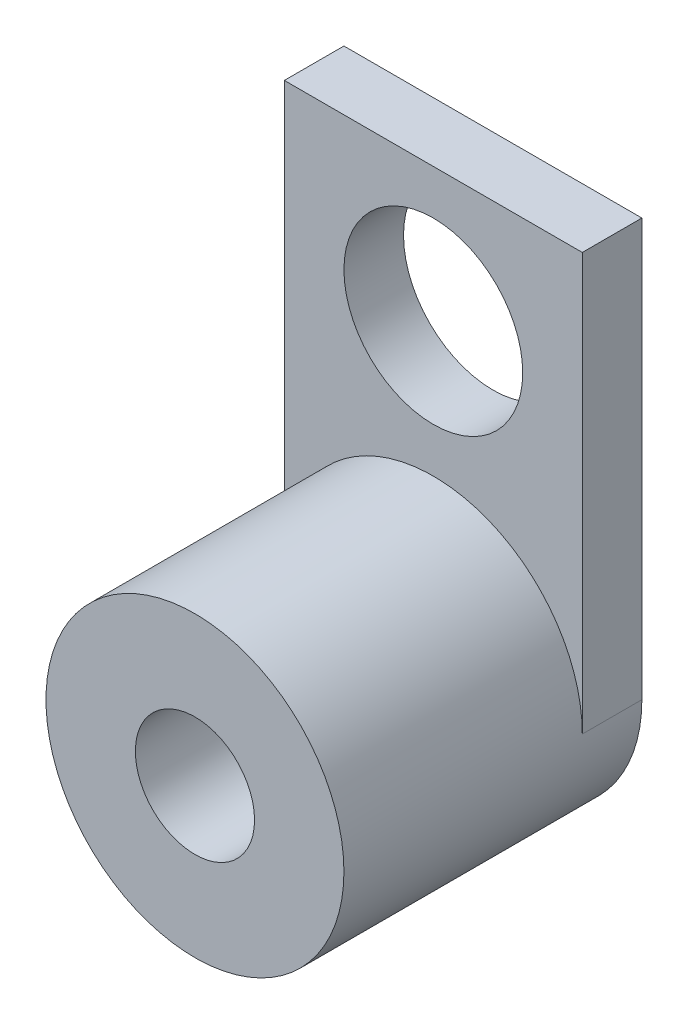
SolidWorks part; units mm, degrees
ref_plane "Front Plane" through (0, 0, 0) normal (1, 0, 0) x (0, 1, 0)
ref_plane "Top Plane" through (0, 0, 0) normal (0, 0, 1) x (0, 1, 0)
ref_plane "Right Plane" through (0, 0, 0) normal (0, 1, 0) x (-1, 0, 0)
sketch "Sketch3" plane through (0, 0, 0) normal (0, 0, 1) x (0, 1, 0)
  circle A0 centre (0, 0) radius 63.5
  circle A1 centre (0, 0) radius 25.4
  dimension "D1" = 127
  dimension "D2" = 50.8
extrude "Boss-Extrude1" add sketch "Sketch3" along normal blind 127
sketch "Sketch4" plane through (0, 0, 0) normal (0, 0, 1) x (0, 1, 0)
  line L1 (0, 63.5) -> (177.8, 63.5)
  line L2 (0, -63.5) -> (177.8, -63.5)
  line L3 (177.8, 63.5) -> (177.8, -63.5)
  line L4 (0, -69.85) -> (0, 69.85) construction
  line L5 (-69.85, 0) -> (69.85, 0) construction
  circle A0 centre (0, 0) radius 63.5 construction
  arc A1 (0, 63.5) -> (0, -63.5) centre (0, 0) ccw
  circle A2 centre (0, 0) radius 25.4 construction
  circle A3 centre (0, 0) radius 25.4
  circle A4 centre (120.65, 0) radius 38.1
  point P2 (0, 0)
  dimension "D2" = 76.2
  dimension "D1" = 177.8
  dimension "D3" = 57.15
extrude "Boss-Extrude2" add sketch "Sketch4" along normal blind 25.4
